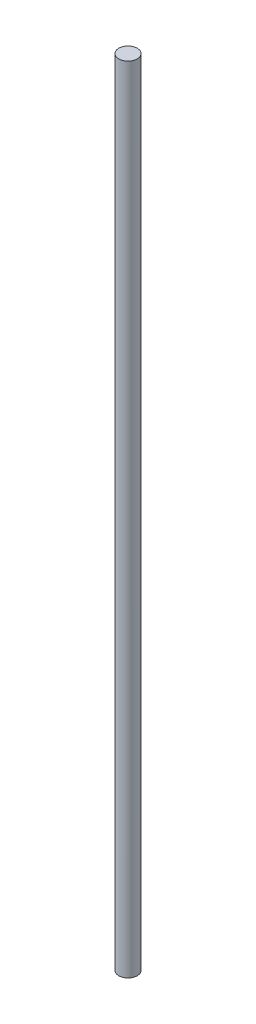
SolidWorks part; units mm, degrees
ref_plane "Front Plane" through (0, 0, 0) normal (0, 0, 1) x (1, 0, 0)
ref_plane "Top Plane" through (0, 0, 0) normal (0, 1, 0) x (1, 0, 0)
ref_plane "Right Plane" through (0, 0, 0) normal (1, 0, 0) x (0, 0, -1)
sketch "Sketch1" plane through (0, 52.3076, 0) normal (0, 1, 0) x (1, 0, 0)
  circle A0 centre (0, 760.2149) radius 12.2493
extrude "Boss-Extrude1" add sketch "Sketch1" along normal blind 1428.75
sketch "Sketch2" plane through (0, 52.3076, 0) normal (0, -1, 0) x (1, 0, 0)
  circle A1 centre (0, -760.2149) radius 12.2493
  circle A2 centre (0, -760.2149) radius 12.2493
  dimension "D1" = 0
extrude "Cut-Extrude1" cut sketch "Sketch2" against normal blind 375.92
